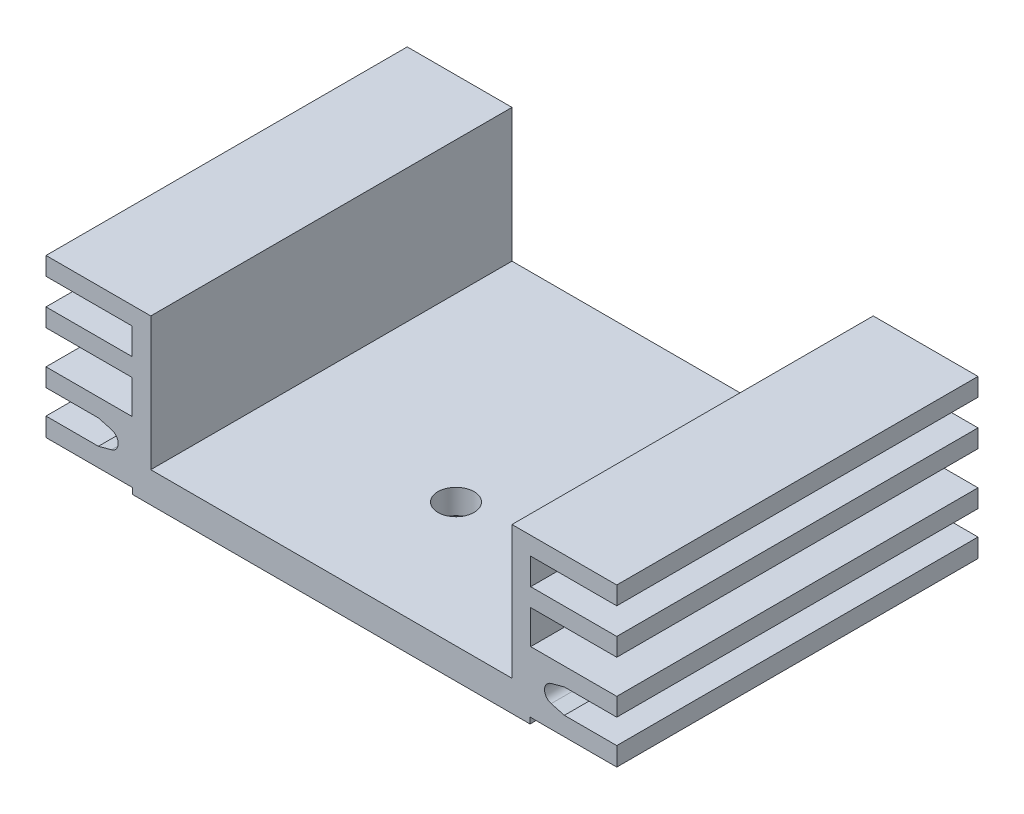
SolidWorks part; units mm, degrees
ref_plane "Front Plane" through (0, 0, 0) normal (0, 0, 1) x (1, 0, 0)
ref_plane "Top Plane" through (0, 0, 0) normal (0, 1, 0) x (1, 0, 0)
ref_plane "Right Plane" through (0, 0, 0) normal (1, 0, 0) x (0, 0, -1)
sketch "Sketch1" plane through (0, 0, 0) normal (0, 0, 1) x (1, 0, 0)
  line L0 (0, 24.3033) -> (0, -14.3062) construction
  line L1 (-15, 13.1) -> (-15, 2.04)
  line L2 (-15, 2.04) -> (15, 2.04)
  line L3 (-15, 13.1) -> (-23.7, 13.1)
  line L4 (-23.7, 13.1) -> (-23.7, 11.6)
  line L5 (-23.7, 11.6) -> (-16.55, 11.6)
  line L6 (16.5, -0.5) -> (-16.5, -0.5)
  line L7 (-16.5, -0.5) -> (-16.5, 0)
  line L8 (-16.5, 0) -> (-23.7, 0)
  line L9 (-23.7, 0) -> (-23.7, 1.55)
  line L10 (-23.7, 9.4) -> (-23.7, 7.9)
  line L11 (-23.7, 7.9) -> (-16.55, 7.9)
  line L12 (-23.7, 9.4) -> (-16.55, 9.4)
  line L13 (-16.55, 9.4) -> (-16.55, 11.6)
  line L14 (-23.7, 1.55) -> (-19.35, 1.55)
  line L15 (-19.35, 1.55) -> (-18.2544, 1.846)
  line L16 (-19.35, 3.59) -> (-23.7, 3.59)
  line L17 (-16.55, 7.9) -> (-16.55, 5.09)
  line L18 (-16.55, 5.09) -> (-23.7, 5.09)
  line L19 (-23.7, 5.09) -> (-23.7, 3.59)
  line L20 (-18.2544, 3.294) -> (-19.35, 3.59)
  line L21 (-23.7, 3.59) -> (-23.7, 1.55) construction
  line L22 (-23.7, 2.57) -> (-16.1511, 2.57) construction
  line L23 (23.7, 2.57) -> (16.1511, 2.57) construction
  line L24 (23.7, 3.59) -> (23.7, 1.55) construction
  line L25 (18.2544, 3.294) -> (19.35, 3.59)
  line L26 (23.7, 5.09) -> (23.7, 3.59)
  line L27 (16.55, 5.09) -> (23.7, 5.09)
  line L28 (16.55, 7.9) -> (16.55, 5.09)
  line L29 (19.35, 3.59) -> (23.7, 3.59)
  line L30 (19.35, 1.55) -> (18.2544, 1.846)
  line L31 (23.7, 1.55) -> (19.35, 1.55)
  line L32 (16.55, 9.4) -> (16.55, 11.6)
  line L33 (23.7, 9.4) -> (16.55, 9.4)
  line L34 (23.7, 7.9) -> (16.55, 7.9)
  line L35 (23.7, 9.4) -> (23.7, 7.9)
  line L36 (23.7, 0) -> (23.7, 1.55)
  line L37 (16.5, 0) -> (23.7, 0)
  line L38 (16.5, -0.5) -> (16.5, 0)
  line L39 (23.7, 11.6) -> (16.55, 11.6)
  line L40 (23.7, 13.1) -> (23.7, 11.6)
  line L41 (15, 13.1) -> (23.7, 13.1)
  line L42 (15, 13.1) -> (15, 2.04)
  arc A0 (-18.2544, 1.846) -> (-18.2544, 3.294) centre (-18.45, 2.57) ccw
  arc A1 (18.2544, 1.846) -> (18.2544, 3.294) centre (18.45, 2.57) cw
  point P47 (0, -0.5)
  point P51 (0, 2.04)
  dimension "D12" = 4.35
  dimension "D13" = 0.75
  dimension "D1" = 47.4
  dimension "D2" = 30
  dimension "D3" = 13.1
  dimension "D4" = 1.5
  dimension "D5" = 7.15
  dimension "D7" = 2.2
  dimension "D8" = 2.54
  dimension "D9" = 0.5
  dimension "D10" = 33
  dimension "D11" = 1.55
  dimension "D14" = 2.04
  dimension "D15" = 5.25
  dimension "D6" = 2
extrude "Boss-Extrude1" add sketch "Sketch1" along normal mid plane 30
sketch "Sketch2" plane through (0, -0.5, 0) normal (0, -1, 0) x (1, 0, 0)
  line L0 (-16.5, 15) -> (16.5, 15) construction
  circle A0 centre (0, 4.65) radius 1.5
  dimension "D1" = 10.35
  dimension "D2" = 3
extrude "Cut-Extrude1" cut sketch "Sketch2" against normal through all
chamfer "Chamfer1" distance 0.5 angle 45 1 edges at (0, -0.5, 3.15)
